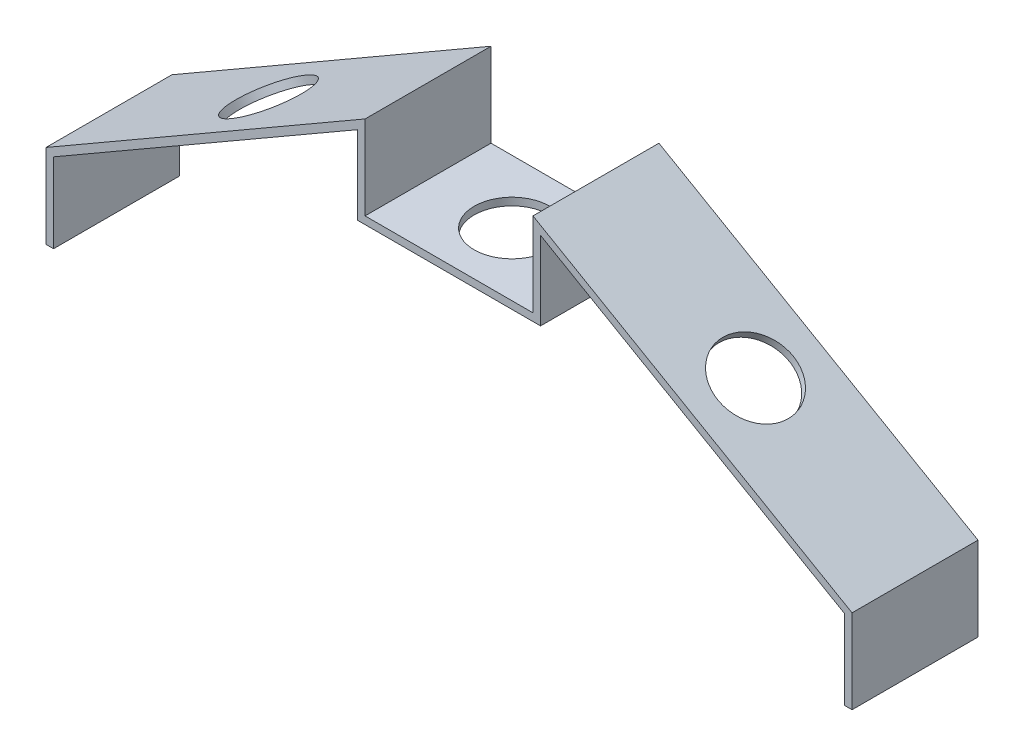
SolidWorks part; units mm, degrees
ref_plane "Alzado" through (0, 0, 0) normal (0, 0, 1) x (1, 0, 0)
ref_plane "Planta" through (0, 0, 0) normal (0, 1, 0) x (1, 0, 0)
ref_plane "Vista lateral" through (0, 0, 0) normal (1, 0, 0) x (0, 0, -1)
sketch "Croquis1" plane through (0, 0, 0) normal (0, 0, 1) x (1, 0, 0)
  line L0 (-20, 0) -> (20, 0)
  line L1 (20, 0) -> (20, 20)
  line L2 (20, 20) -> (96, -23.8786)
  line L3 (96, -23.8786) -> (96, -43.8786)
  line L4 (-20, 0) -> (-20, 20)
  line L5 (-20, 20) -> (-96, -23.8786)
  line L6 (-96, -23.8786) -> (-96, -43.8786)
  line L7 (-94.2, -24.9179) -> (-94.2, -43.8786)
  line L8 (-21.8, 16.8823) -> (-94.2, -24.9179)
  line L9 (-21.8, -1.8) -> (-21.8, 16.8823)
  line L10 (-21.8, -1.8) -> (21.8, -1.8)
  line L11 (21.8, -1.8) -> (21.8, 16.8823)
  line L12 (21.8, 16.8823) -> (94.2, -24.9179)
  line L13 (94.2, -24.9179) -> (94.2, -43.8786)
  line L14 (94.2, -43.8786) -> (96, -43.8786)
  line L15 (-94.2, -43.8786) -> (-96, -43.8786)
  point P7 (0, 0)
  dimension "D1" = 40
  dimension "D2" = 192
  dimension "D3" = 20
  dimension "D4" = 30
  dimension "D5" = 20
  dimension "D6" = 1.8
extrude "Saliente-Extruir1" add sketch "Croquis1" along normal blind 30
sketch "Croquis2" plane through (0, 0, 0) normal (0, 1, 0) x (1, 0, 0)
  line L0 (-20, -30) -> (-20, 0) construction
  circle A0 centre (0, -15) radius 9
  point P2 (0, 0)
  point P4 (0, 0)
  point P7 (-20, -15)
  dimension "D1" = 18
extrude "Cortar-Extruir1" cut sketch "Croquis2" against normal through all
sketch "Croquis3" plane through (13.6603, 23.6603, 0) normal (0.5, 0.866, 0) x (0.866, -0.5, 0)
  line L1 (7.3205, 0) -> (95.0777, -30) construction
  circle A0 centre (51.1991, -15) radius 9
  point P4 (0, 0)
  point P5 (51.1991, -15)
  dimension "D1" = 18
extrude "Cortar-Extruir2" cut sketch "Croquis3" against normal blind 30
sketch "Croquis4" plane through (-13.6603, 23.6603, 0) normal (-0.5, 0.866, 0) x (0.866, 0.5, 0)
  line L0 (-95.0777, 0) -> (-7.3205, -30) construction
  circle A0 centre (-51.1991, -15) radius 9
  dimension "D1" = 18
extrude "Cortar-Extruir3" cut sketch "Croquis4" against normal blind 30
